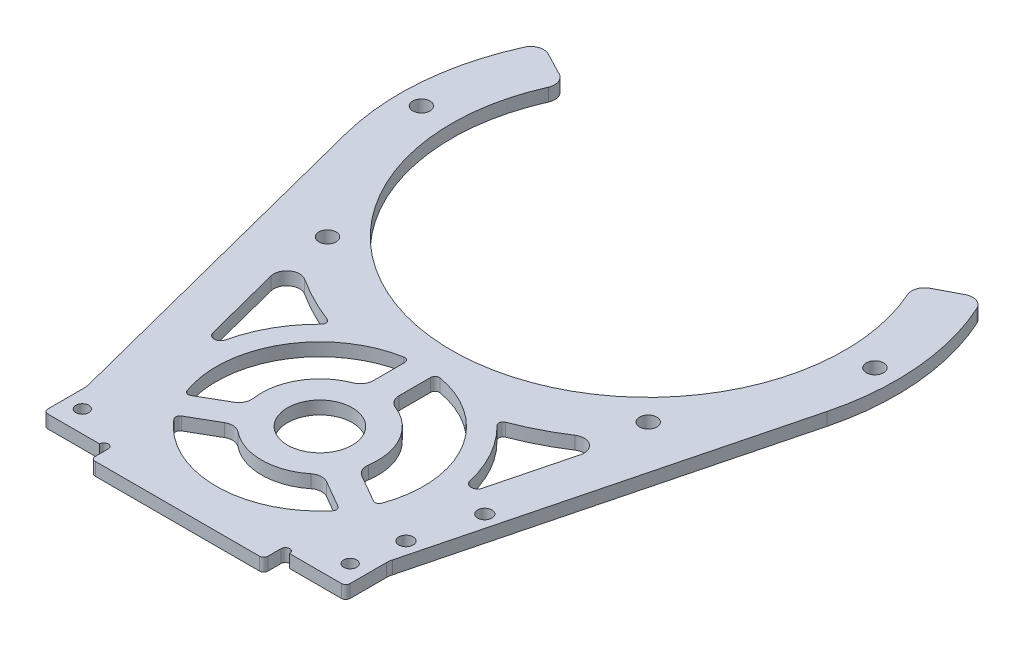
SolidWorks part; units mm, degrees
material "Thornel Mat VMA"
ref_plane "前视基准面" through (0, 0, 0) normal (0, 0, 1) x (1, 0, 0)
ref_plane "上视基准面" through (0, 0, 0) normal (0, 1, 0) x (1, 0, 0)
ref_plane "右视基准面" through (0, 0, 0) normal (1, 0, 0) x (0, 0, -1)
sketch "草图1" plane through (0, 0, 0) normal (0, 1, 0) x (1, 0, 0)
  line L5 (-51.0031, 26.5505) -> (-40.359, 21.0096)
  line L15 (0, -1.65) -> (0, 1.65) construction
  line L25 (51.0031, 26.5505) -> (40.359, 21.0096)
  line L29 (-55.698, -14.2823) -> (-35, -95)
  line L30 (-35, -95) -> (-35, -105)
  line L31 (-35, -105) -> (-20, -105)
  line L32 (35, -95) -> (35, -105)
  line L33 (55.698, -14.2823) -> (35, -95)
  line L34 (20, -105) -> (35, -105)
  line L36 (-20, -105) -> (-20, -109)
  line L37 (-20, -109) -> (20, -109)
  line L39 (20, -105) -> (20, -109)
  line L51 (0, -58) -> (0, 0) construction
  line L52 (32.9253, -89) -> (36.6511, -74.4701) construction
  circle A20 centre (0, 0) radius 52.5 construction
  circle A32 centre (-31, -100) radius 1.5
  circle A34 centre (31, -100) radius 1.5
  arc A36 (-51.0031, 26.5505) -> (-55.698, -14.2823) centre (0, 0) ccw
  arc A37 (-40.359, 21.0096) -> (40.359, 21.0096) centre (0, 0) ccw
  arc A38 (51.0031, 26.5505) -> (55.698, -14.2823) centre (0, 0) cw
  circle A39 centre (0, -52.5) radius 2 construction
  circle A40 centre (-37.1231, -37.1231) radius 2
  circle A41 centre (-52.5, 0) radius 2
  circle A42 centre (-37.1231, 37.1231) radius 2 construction
  circle A43 centre (0, 52.5) radius 2 construction
  circle A44 centre (37.1231, 37.1231) radius 2 construction
  circle A45 centre (52.5, 0) radius 2
  circle A46 centre (37.1231, -37.1231) radius 2
  circle A48 centre (32.9253, -89) radius 1.65
  circle A49 centre (36.6511, -74.4701) radius 1.65
  dimension "D3" = 105
  dimension "D5" = 10
  dimension "D6" = 91
  dimension "D7" = 4
  dimension "D8" = 8
  dimension "D9" = 105
  dimension "D10" = 70
  dimension "D4" = 5
  dimension "D23" = 3
  dimension "D24" = 3.5
  dimension "D25" = 3.3
  dimension "D26" = 16
  dimension "D14" = 5
  dimension "D17" = 4
  dimension "D11" = 125
  dimension "D13" = 58
  dimension "D15" = 40
  dimension "D16" = 4
  dimension "D18" = 15
extrude "凸台-拉伸1" add sketch "草图1" along normal blind 3
sketch "草图3" plane through (0, 3, 0) normal (0, 1, 0) x (1, 0, 0)
  line L0 (-35, -105) -> (-20, -105) construction
  line L1 (20, -105) -> (35, -105) construction
  circle A8 centre (-21, -105) radius 1
  circle A9 centre (21, -105) radius 1
  dimension "D1" = 2
extrude "切除-拉伸3" cut sketch "草图3" against normal through all
sketch "草图4" plane through (0, 3, 0) normal (0, 1, 0) x (1, 0, 0)
  line L17 (-55.698, -14.2823) -> (-35, -95) construction
  line L19 (-35.8305, -51.5017) -> (-31.1907, -69.5961)
  line L23 (0, -1.65) -> (0, 1.65) construction
  line L28 (-20, -109) -> (20, -109) construction
  line L29 (35.8305, -51.5017) -> (31.1907, -69.5961)
  arc A0 (-31.2919, -48.2397) -> (-19.1462, -54.2188) centre (0, 0) ccw
  arc A2 (-40.359, 21.0096) -> (40.359, 21.0096) centre (0, 0) ccw construction
  arc A5 (-35.8305, -51.5017) -> (-31.2919, -48.2397) centre (-32.9245, -50.7565) cw
  arc A7 (19.1462, -54.2188) -> (28.2752, -69.5567) centre (0, -76) cw
  circle A9 centre (0, -76) radius 24
  arc A11 (-19.1462, -54.2188) -> (-28.2752, -69.5567) centre (0, -76) ccw
  arc A12 (35.8305, -51.5017) -> (31.2919, -48.2397) centre (32.9245, -50.7565) ccw
  arc A13 (31.2919, -48.2397) -> (19.1462, -54.2188) centre (0, 0) cw
  circle A14 centre (0, -76) radius 13.5
  circle A15 centre (0, -76) radius 7.5
  arc A16 (-28.2752, -69.5567) -> (-31.1907, -69.5961) centre (-29.7377, -69.2235) cw
  arc A17 (28.2752, -69.5567) -> (31.1907, -69.5961) centre (29.7377, -69.2235) ccw
  dimension "D8" = 6
  dimension "D1" = 12
  dimension "D4" = 3
  dimension "D2" = 10
  dimension "D5" = 33
  dimension "D6" = 5
  dimension "D7" = 15
  dimension "D3" = 48
  dimension "D9" = 1.5
extrude "切除-拉伸4" cut sketch "草图4" against normal through all contours A11 A0 A5 L19 | A12 A13 A7 L29 | A9 A14 | A15
sketch "草图5" plane through (0, 3, 0) normal (0, 1, 0) x (1, 0, 0)
  line L0 (0, -52) -> (0, -68.5)
  line L1 (20.7846, -88) -> (6.4952, -79.75)
  line L2 (-20.7846, -88) -> (-6.4952, -79.75)
  circle A0 centre (0, -76) radius 24 construction
  circle A1 centre (0, -76) radius 7.5 construction
  dimension "D1" = 3
extrude "拉伸-薄壁1" add sketch "草图5" against normal up to surface (3 mm away) thin up to face at (0, 0, 100) thin type mid plane wall 6
fillet "圆角4" radius 1 12 edges at (-35, 1.5, 105) (35, 1.5, 105) (20, 1.5, 109) (-20, 1.5, 109) (19.1462, 1.5, 54.2188) (-19.1462, 1.5, 54.2188) (-3, 1.5, 52.1882) (3, 1.5, 52.1882) (22.1216, 1.5, 85.3078) (19.1216, 1.5, 90.504) (-19.1216, 1.5, 90.504) (-22.1216, 1.5, 85.3078)
fillet "圆角6" radius 5 2 edges at (35, 1.5, 95) (-35, 1.5, 95)
fillet "圆角7" radius 3 10 edges at (40.359, 1.5, -21.0096) (51.0031, 1.5, -26.5505) (-40.359, 1.5, -21.0096) (-51.0031, 1.5, -26.5505) (12.899, 1.5, 79.9831) (3, 1.5, 62.8376) (-3, 1.5, 62.8376) (-9.899, 1.5, 85.1793) (9.899, 1.5, 85.1793) (-12.899, 1.5, 79.9831)
